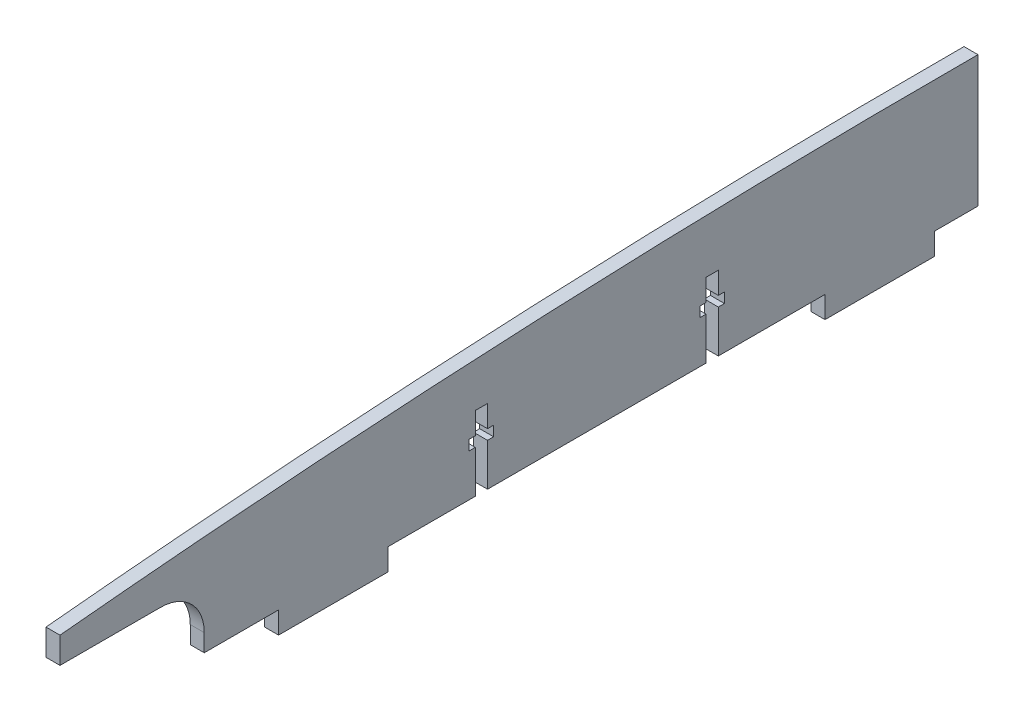
SolidWorks part; units mm, degrees
ref_plane "Front Plane" through (0, 0, 0) normal (0, 0, 1) x (1, 0, 0)
ref_plane "Top Plane" through (0, 0, 0) normal (0, 1, 0) x (1, 0, 0)
ref_plane "Right Plane" through (0, 0, 0) normal (1, 0, 0) x (0, 0, -1)
sketch "Sketch1" plane through (0, 0, 0) normal (1, 0, 0) x (0, 0, -1)
  line L0 (-87.5354, 0) -> (122.4646, 0)
  line L1 (122.4646, 0) -> (122.4646, 30)
  line L2 (-87.5354, 0) -> (-87.5354, 20)
  line L3 (122.4646, 30) -> (8.5435, 30) construction
  spline S0 degree 2 poles (-87.5354, 20) (17.331, 30.2969) (122.4646, 30) knots 0 0 0 1 1 1
  point P11 (110.6793, 30)
  dimension "D1" = 210
  dimension "D2" = 30
  dimension "D3" = 20
extrude "main" add sketch "Sketch1" along normal blind 3.2
sketch "Sketch2" plane through (3.2, 0, 0) normal (1, 0, 0) x (0, 0, -1)
  line L3 (-87.5354, 0) -> (-54.5354, 0)
  line L4 (-87.5354, 0) -> (-87.5354, 14)
  line L5 (-87.5354, 14) -> (-64.5354, 14)
  line L6 (-54.5354, 0) -> (-54.5354, 4)
  arc A1 (-54.5354, 4) -> (-64.5354, 14) centre (-64.5354, 4) ccw
  dimension "D1" = 10
  dimension "D2" = 33
  dimension "D3" = 14
extrude "wheel" cut sketch "Sketch2" against normal blind 3.2
sketch "Sketch3" plane through (3.2, 0, 0) normal (1, 0, 0) x (0, 0, -1)
  line L0 (-54.5354, 0) -> (122.4646, 0) construction
  line L1 (-37.5354, 0) -> (-12.5354, 0)
  line L2 (-37.5354, 0) -> (-37.5354, -5)
  line L3 (-37.5354, -5) -> (-12.5354, -5)
  line L4 (-12.5354, 0) -> (-12.5354, -5)
  line L5 (87.4646, 0) -> (87.4646, -5)
  line L6 (87.4646, 0) -> (112.4646, 0)
  line L7 (112.4646, 0) -> (112.4646, -5)
  line L8 (87.4646, -5) -> (112.4646, -5)
  line L9 (-87.5354, 20) -> (-87.5354, 14) construction
  dimension "D2" = 25
  dimension "D3" = 5
  dimension "D4" = 50
  dimension "D5" = 100
  dimension "D1" = 2
extrude "tabs" add sketch "Sketch3" against normal up to surface (3.2 mm away) up to face at (0, 12.7244, -0.4747)
sketch "Sketch5" plane through (3.2, 0, 0) normal (1, 0, 0) x (0, 0, -1)
  line L0 (-12.5354, 0) -> (87.4646, 0) construction
  line L1 (7.4646, 0) -> (10.2646, 0)
  line L2 (7.4646, 0) -> (7.4646, 9.7)
  line L3 (7.4646, 17) -> (10.2646, 17)
  line L4 (10.2646, 0) -> (10.2646, 9.7)
  line L5 (7.4646, 12) -> (7.4646, 17)
  line L6 (6.0646, 12) -> (7.4646, 12)
  line L7 (6.0646, 12) -> (6.0646, 9.7)
  line L8 (6.0646, 9.7) -> (7.4646, 9.7)
  line L9 (11.6646, 12) -> (11.6646, 9.7)
  line L10 (10.2646, 12) -> (11.6646, 12)
  line L11 (10.2646, 12) -> (10.2646, 17)
  line L12 (10.2646, 9.7) -> (11.6646, 9.7)
  line L13 (60.2646, 0) -> (63.0646, 0)
  line L14 (60.2646, 0) -> (60.2646, 9.7)
  line L15 (60.2646, 17) -> (63.0646, 17)
  line L16 (63.0646, 0) -> (63.0646, 9.7)
  line L17 (60.2646, 12) -> (60.2646, 17)
  line L18 (58.8646, 12) -> (60.2646, 12)
  line L19 (58.8646, 12) -> (58.8646, 9.7)
  line L20 (58.8646, 9.7) -> (60.2646, 9.7)
  line L21 (64.4646, 12) -> (64.4646, 9.7)
  line L22 (63.0646, 12) -> (64.4646, 12)
  line L23 (63.0646, 12) -> (63.0646, 17)
  line L24 (63.0646, 9.7) -> (64.4646, 9.7)
  line L25 (-12.5354, -5) -> (-12.5354, 0) construction
  dimension "D1" = 2.3
  dimension "D2" = 2.8
  dimension "D3" = 5
  dimension "D4" = 17
  dimension "D6" = 20
  dimension "D7" = 5.6
  dimension "D8" = 50
  dimension "D5" = 2
extrude "screw holes" cut sketch "Sketch5" against normal up to surface (3.2 mm away) up to face at (0, 4.6047, -20.2026)
sketch "Sketch6" plane through (3.2, 0, 0) normal (1, 0, 0) x (0, 0, -1)
  line L0 (-54.5354, 0) -> (-37.5354, 0) construction
  line L1 (-42.5354, 15) -> (-27.5354, 15)
  line L2 (-42.5354, 15) -> (-42.5354, 5)
  line L3 (-42.5354, 5) -> (-27.5354, 5)
  line L4 (-27.5354, 15) -> (-27.5354, 5)
  dimension "D1" = 10
  dimension "D2" = 15
  dimension "D3" = 12
  dimension "D4" = 5
